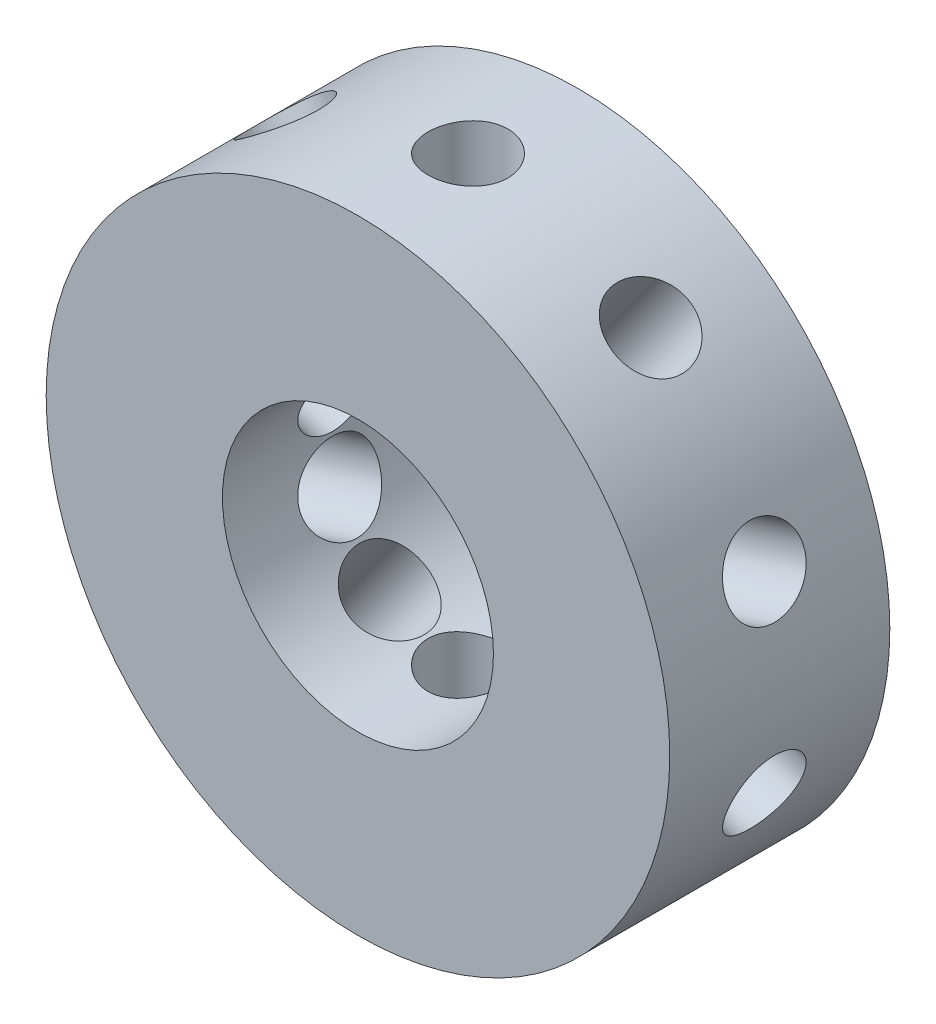
SolidWorks part; units mm, degrees
ref_plane "Front Plane" through (0, 0, 0) normal (0, 0, 1) x (1, 0, 0)
ref_plane "Top Plane" through (0, 0, 0) normal (0, 1, 0) x (1, 0, 0)
ref_plane "Right Plane" through (0, 0, 0) normal (1, 0, 0) x (0, 0, -1)
sketch "Sketch1" plane through (0, 0, 0) normal (0, 0, 1) x (1, 0, 0)
  circle A0 centre (0, 0) radius 29.75
  circle A1 centre (0, 0) radius 12.928
  dimension "D1" = 59.5
extrude "Boss-Extrude1" add sketch "Sketch1" along normal blind 21 contours A0 | A1
sketch "Sketch3" plane through (0, 0, 0) normal (0, 1, 0) x (1, 0, 0)
  line L0 (0, 0) -> (0, -21) construction
  line L1 (-29.75, -21) -> (29.75, -21) construction
  circle A0 centre (0, -10.5) radius 3.81
  dimension "D1" = 7.62
extrude "Cut-Extrude1" cut sketch "Sketch3" against normal blind 31
ref_axis "Axis1" through (0, 0, 21) along (0, 0, -1)
pattern_circular "CirPattern1" count 10 over 360 about axis through (0, 0, 21) along (0, 0, -1) of "Cut-Extrude1"
